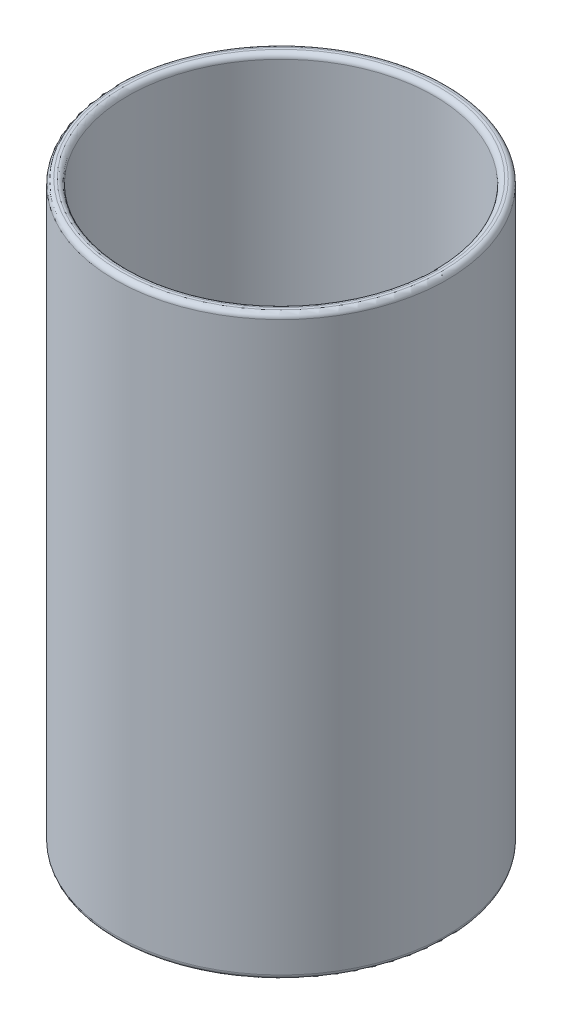
SolidWorks part; units mm, degrees
material "ABS"
ref_plane "Front Plane" through (0, 0, 0) normal (0, 0, 1) x (1, 0, 0)
ref_plane "Top Plane" through (0, 0, 0) normal (0, 1, 0) x (1, 0, 0)
ref_plane "Right Plane" through (0, 0, 0) normal (1, 0, 0) x (0, 0, -1)
sketch "Sketch2" plane through (0, 0, 0) normal (0, 1, 0) x (1, 0, 0)
  circle A0 centre (0, 0) radius 33
  circle A1 centre (0, 0) radius 30.5
  dimension "D1" = 66
  dimension "D2" = 61
extrude "Boss-Extrude1" add sketch "Sketch2" along normal blind 115
fillet "Fillet1" radius 1 4 edges at (0, 0, 30.5) (0, 0, 33) (0, 115, 30.5) (0, 115, 33)
